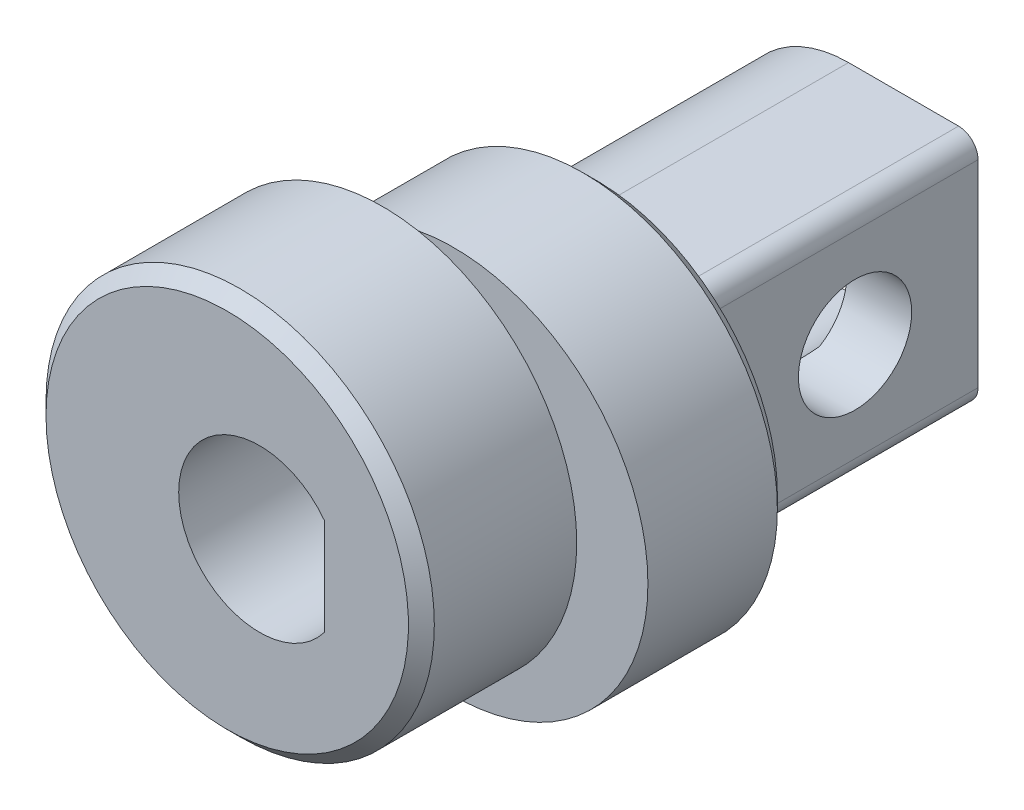
SolidWorks part; units mm, degrees
ref_plane "Ebene vorne" through (0, 0, 0) normal (0, 0, 1) x (1, 0, 0)
ref_plane "Ebene oben" through (0, 0, 0) normal (0, 1, 0) x (1, 0, 0)
ref_plane "Ebene rechts" through (0, 0, 0) normal (1, 0, 0) x (0, 0, -1)
ref_plane "Plane2" through (0, 0, 0.4) normal (0, 0, 1) x (1, 0, 0)
sketch "Sketch10" plane through (0, 0, 0.4) normal (0, 0, 1) x (1, 0, 0)
  circle A0 centre (1.2, 0) radius 6
  dimension "D1" = 12
extrude "Boss-Extrude4" add sketch "Sketch10" along normal blind 4.2 and the other way blind 0.2
sketch "Sketch11" plane through (0, 0, 0.2) normal (0, 0, -1) x (-1, 0, 0)
  line L0 (-4, -3.05) -> (-4, 3.05)
  line L1 (-3.4, 3.65) -> (0, 3.65)
  line L2 (0, -3.65) -> (-3.4, -3.65)
  arc A2 (0, 3.65) -> (0, -3.65) centre (0, 0) cw
  arc A3 (-4, 3.05) -> (-3.4, 3.65) centre (-3.4, 3.05) cw
  arc A4 (-3.4, -3.65) -> (-4, -3.05) centre (-3.4, -3.05) cw
  point P0 (0, 3.65)
  point P3 (0, 0)
  point P9 (0, -0.5971)
  point P11 (0, 0)
  point P12 (-4, 2.7302)
  dimension "D1" = 3.65
  dimension "D3" = 0.6
  dimension "D2" = 4
extrude "Boss-Extrude5" add sketch "Sketch11" along normal blind 9
ref_plane "Plane3" through (0, 0, 4.6) normal (0, 0, -1) x (-1, 0, 0)
sketch "Sketch16" plane through (0, 0, 4.6) normal (0, 0, -1) x (-1, 0, 0)
  circle A0 centre (1, 0) radius 6
  point P2 (0, 0)
  dimension "D1" = 12
  dimension "D2" = 1
extrude "Boss-Extrude6" add sketch "Sketch16" against normal blind 4.8
sketch "Sketch17" plane through (0, 0, 9.4) normal (0, 0, 1) x (1, 0, 0)
  line L0 (2, -1.5) -> (2, 1.5)
  line L1 (-2.5, 0) -> (-2.5, 1.4955) construction
  arc A0 (2, 1.5) -> (2, -1.5) centre (0, 0) ccw
  point P5 (0, 0)
  point P7 (0, 0)
  dimension "D1" = 2.5
  dimension "D2" = 4.5
extrude "Cut-Extrude2" cut sketch "Sketch17" against normal through all
hole_wizard "Ø3.5 (3.5) Diameter Hole0" positions "Sketch19" profile "Sketch18" hole size "Ø3.5" standard "ANSI Metric"
sketch "Sketch19" plane through (4, 0, 0) normal (1, 0, 0) x (0, 0, -1)
  point P0 (5, 0)
sketch "Sketch18" plane through (4, 0, -5) normal (0, 1, 0) x (0, 0, -1)
  line L0 (0, 0) -> (0, 5.0515)
  line L1 (0, 5.0515) -> (1.75, 4)
  line L2 (1.75, 4) -> (1.75, 0)
  line L5 (1.75, 0) -> (0, 0)
  line L10 (0, 5.0515) -> (-1.75, 4) construction
  line L11 (0, -6.35) -> (0, 107.95) construction
  dimension "Hole Dia." = 3.5
  dimension "Hole Depth" = 4
  dimension "Drill Angle" = 118
chamfer "Chamfer2" distance 0.4 angle 45 2 edges at (-7, 0, 9.4) (7.2, 0, 0.2)
